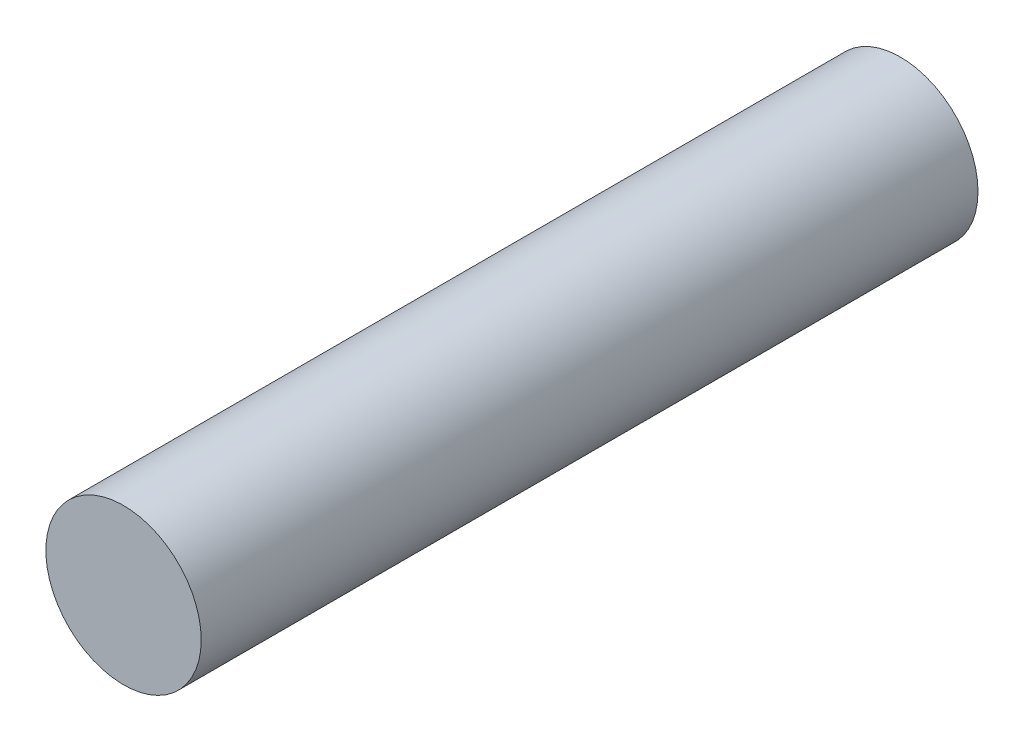
SolidWorks part; units mm, degrees
ref_plane "Front Plane" through (0, 0, 0) normal (0, 0, 1) x (1, 0, 0)
ref_plane "Top Plane" through (0, 0, 0) normal (0, 1, 0) x (1, 0, 0)
ref_plane "Right Plane" through (0, 0, 0) normal (1, 0, 0) x (0, 0, -1)
sketch "Sketch1" plane through (0, 0, 0) normal (0, 0, 1) x (1, 0, 0)
  circle A0 centre (0, 0) radius 5
  dimension "D1" = 10
extrude "Boss-Extrude1" add sketch "Sketch1" along normal blind 50
